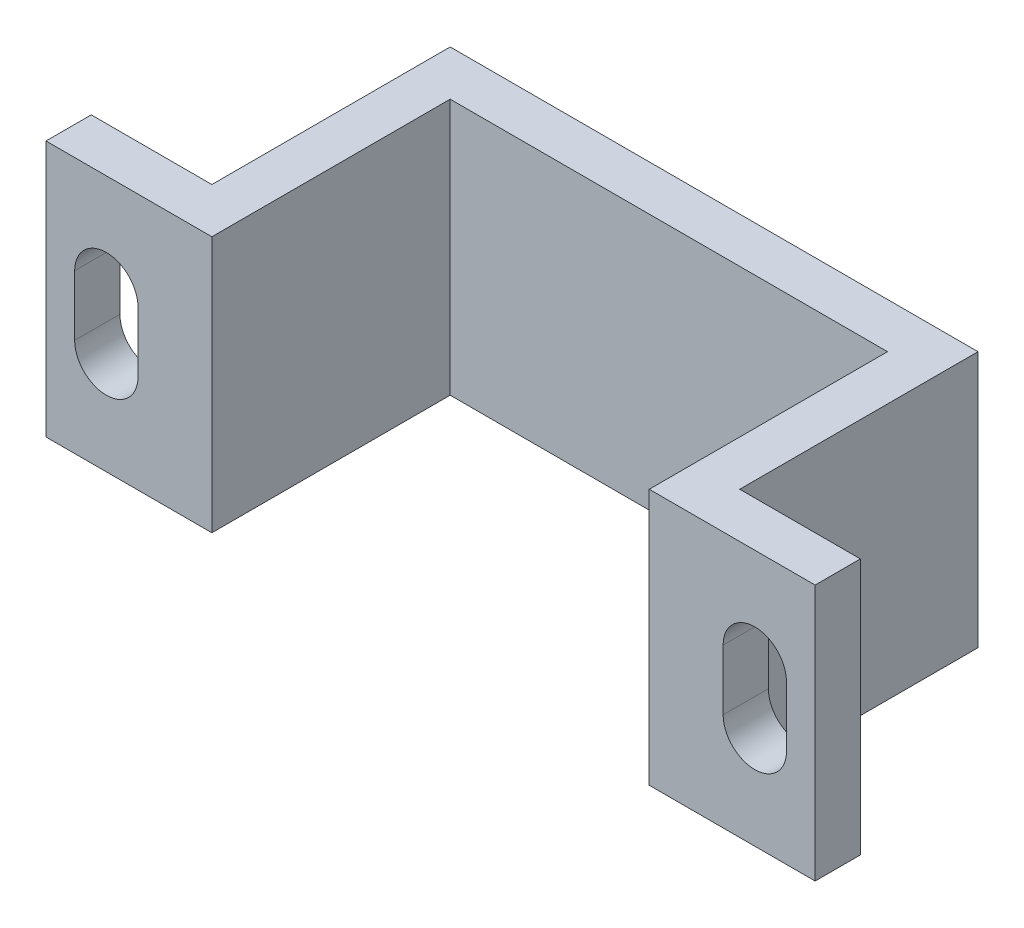
SolidWorks part; units mm, degrees
ref_plane "Front Plane" through (0, 0, 0) normal (0, 0, 1) x (1, 0, 0)
ref_plane "Top Plane" through (0, 0, 0) normal (0, 1, 0) x (1, 0, 0)
ref_plane "Right Plane" through (0, 0, 0) normal (1, 0, 0) x (0, 0, -1)
sketch "Sketch4" plane through (0, 0, 0) normal (0, 1, 0) x (1, 0, 0)
  line L0 (0, 0) -> (13.97, 0)
  line L1 (13.97, 0) -> (13.97, 20.066)
  line L2 (13.97, 20.066) -> (32.385, 20.066)
  line L3 (32.385, 20.066) -> (32.385, 23.876)
  line L4 (32.385, 23.876) -> (10.16, 23.876)
  line L5 (10.16, 23.876) -> (10.16, 3.81)
  line L6 (10.16, 3.81) -> (0, 3.81)
  line L7 (0, 3.81) -> (0, 0)
  line L8 (10.16, 3.81) -> (13.97, 3.81) construction
  line L9 (13.97, 20.066) -> (13.97, 23.876) construction
  dimension "D1" = 3.81
  dimension "D2" = 20.066
  dimension "D3" = 10.16
  dimension "D4" = 18.415
extrude "base" add sketch "Sketch4" along normal blind 21.59
sketch "Sketch5" plane through (0, 0, -3.81) normal (0, 0, -1) x (-1, 0, 0)
  line L0 (-5.08, 13.335) -> (-5.08, 8.255) construction
  line L1 (-2.413, 13.335) -> (-2.413, 8.255)
  line L2 (-7.747, 13.335) -> (-7.747, 8.255)
  line L6 (-10.16, 21.59) -> (-10.16, 0) construction
  line L7 (-10.16, 21.59) -> (0, 21.59) construction
  arc A0 (-2.413, 13.335) -> (-7.747, 13.335) centre (-5.08, 13.335) ccw
  arc A1 (-7.747, 8.255) -> (-2.413, 8.255) centre (-5.08, 8.255) ccw
  point P2 (-5.08, 10.795)
  dimension "D1" = 5.334
  dimension "D2" = 5.08
  dimension "D3" = 5.08
  dimension "D4" = 10.795
extrude "bolthole" cut sketch "Sketch5" against normal up to next
mirror "Mirror1" about plane through (32.385, 21.59, -20.066) normal (-1, 0, 0) of "bolthole", "base"
